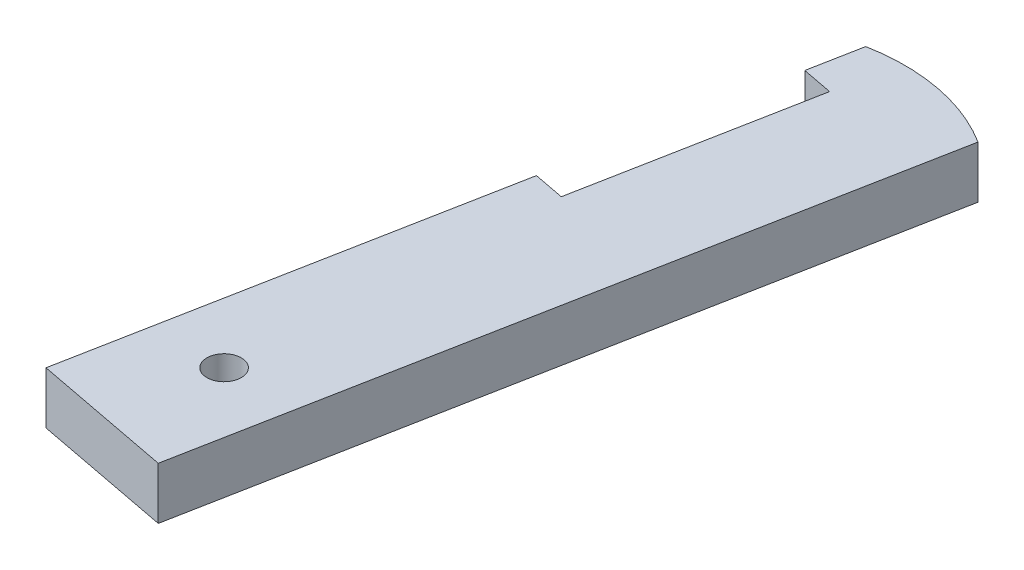
SolidWorks part; units mm, degrees
ref_plane "Front Plane" through (0, 0, 0) normal (0, 0, 1) x (1, 0, 0)
ref_plane "Top Plane" through (0, 0, 0) normal (0, 1, 0) x (1, 0, 0)
ref_plane "Right Plane" through (0, 0, 0) normal (1, 0, 0) x (0, 0, -1)
sketch "Sketch1" plane through (0, 0, 0) normal (0, 1, 0) x (1, 0, 0)
  line L0 (0, 0) -> (0, 50000) construction
  line L1 (3.4777, 18.1702) -> (-18.5162, -96.744) construction
  line L2 (-3.4234, 18.1805) -> (-4.3633, 13.2696)
  line L3 (9.8948, 15.6315) -> (-2.7399, -50.3831)
  line L4 (-16.0582, -47.8341) -> (-2.7399, -50.3831)
  line L5 (-8.4989, -8.3382) -> (-5.5524, -8.9021)
  line L6 (-5.5524, -8.9021) -> (-1.4168, 12.7057)
  line L7 (-1.4168, 12.7057) -> (-4.3633, 13.2696)
  line L8 (-8.4989, -8.3382) -> (-16.0582, -47.8341)
  arc A0 (0, -18.5) -> (-9.8948, -15.6315) centre (0, 0) ccw construction
  arc A1 (9.8948, 15.6315) -> (-3.4234, 18.1805) centre (0, 0) ccw
  circle A2 centre (-7.5193, -39.2869) radius 1.65
  point P11 (-7.5193, -39.2869)
  dimension "D1" = 37
  dimension "D6" = 3.3
  dimension "D2" = 13.56
  dimension "D3" = 40
  dimension "D4" = 10
  dimension "D5" = 10.835
  dimension "D7" = 5
  dimension "D8" = 22
  dimension "D9" = 3
extrude "Boss-Extrude1" add sketch "Sketch1" along normal blind 5
